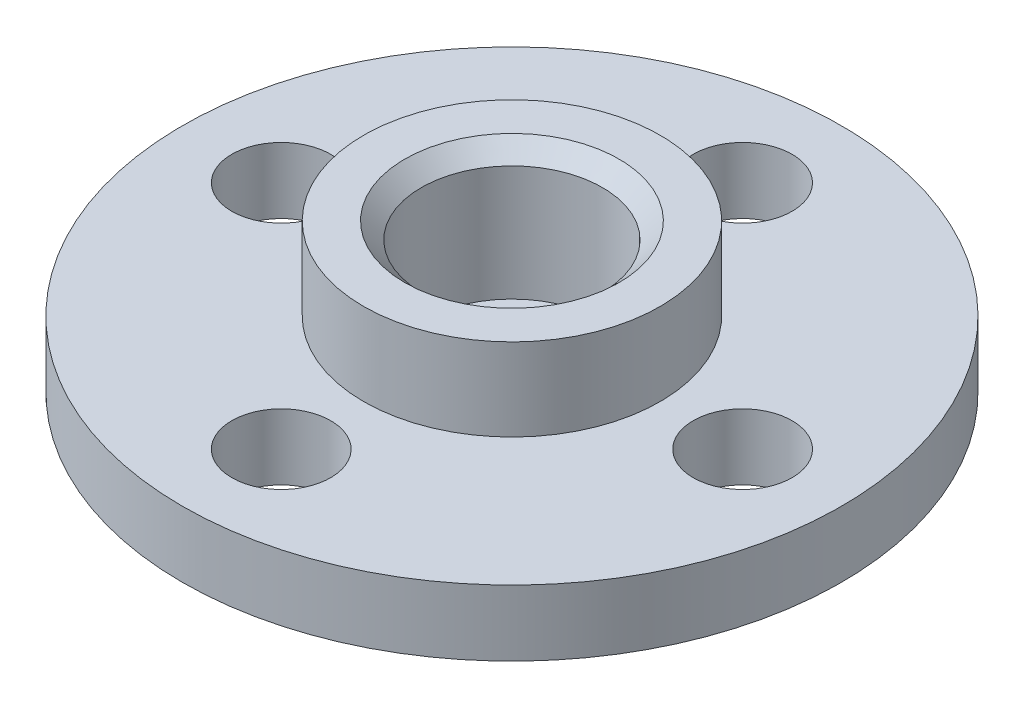
SolidWorks part; units mm, degrees
ref_plane "前视基准面" through (0, 0, 0) normal (0, 0, 1) x (1, 0, 0)
ref_plane "上视基准面" through (0, 0, 0) normal (0, 1, 0) x (1, 0, 0)
ref_plane "右视基准面" through (0, 0, 0) normal (1, 0, 0) x (0, 0, -1)
sketch "草图1" plane through (0, 0, 0) normal (0, 1, 0) x (1, 0, 0)
  circle A0 centre (0, 0) radius 10
  dimension "D1" = 20
extrude "凸台-拉伸1" add sketch "草图1" along normal blind 2
sketch "草图2" plane through (0, 2, 0) normal (0, 1, 0) x (1, 0, 0)
  line L0 (-10, 0) -> (10, 0) construction
  line L1 (0, -10) -> (0, 10) construction
  circle A1 centre (0, 0) radius 10 construction
  circle A2 centre (-7, 0) radius 1.5
  circle A3 centre (0, 7) radius 1.5
  circle A4 centre (7, 0) radius 1.5
  circle A5 centre (0, -7) radius 1.5
  point P21 (0, 0)
  dimension "D2" = 3
  dimension "D4" = 4
sketch "草图3" plane through (0, 2, 0) normal (0, 1, 0) x (1, 0, 0)
  circle A0 centre (0, 0) radius 4.5
  dimension "D1" = 9
extrude "切除-拉伸1" cut sketch "草图2" against normal blind 2
extrude "凸台-拉伸2" add sketch "草图3" along normal blind 2.5
sketch "草图4" plane through (0, 4.5, 0) normal (0, 1, 0) x (1, 0, 0)
  circle A0 centre (0, 0) radius 2.75
  dimension "D1" = 5.5
extrude "切除-拉伸2" cut sketch "草图4" against normal blind 4
sketch "草图5" plane through (0, 0.5, 0) normal (0, 1, 0) x (1, 0, 0)
  circle A0 centre (0, 0) radius 1.5
extrude "切除-拉伸3" cut sketch "草图5" against normal blind 4
chamfer "倒角1" distance 0.5 angle 45 1 edges at (0, 4.5, 2.75)
